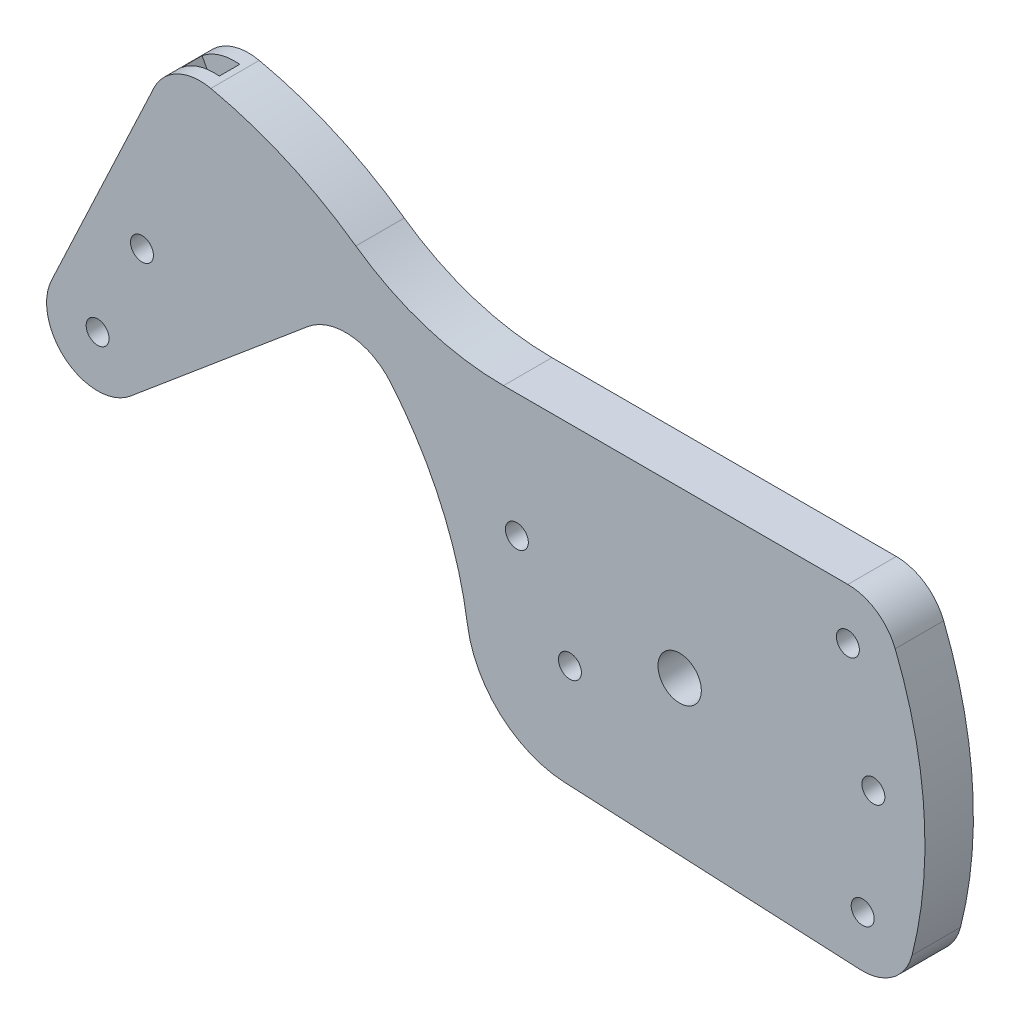
SolidWorks part; units mm, degrees
ref_plane "Front Plane" through (0, 0, 0) normal (0, 0, 1) x (1, 0, 0)
ref_plane "Top Plane" through (0, 0, 0) normal (0, 1, 0) x (1, 0, 0)
ref_plane "Right Plane" through (0, 0, 0) normal (1, 0, 0) x (0, 0, -1)
sketch "Sketch1" plane through (0, 0, 0) normal (0, 0, 1) x (1, 0, 0)
  line L1 (-4.25, -4.25) -> (4.25, -4.25) construction
  line L2 (-4.25, -4.25) -> (-4.25, 4.25) construction
  line L3 (-4.25, 4.25) -> (4.25, 4.25) construction
  line L4 (4.25, -4.25) -> (4.25, 4.25) construction
  line L5 (-4.25, -4.25) -> (4.25, 4.25) construction
  line L6 (-4.25, 4.25) -> (4.25, -4.25) construction
  line L7 (35.3984, -31.7883) -> (-22.5002, -28.984)
  line L9 (-114.4671, 24.4556) -> (-123.1671, 5.9556)
  line L10 (-107.6899, -5.9604) -> (-72.8648, 23.2613)
  line L11 (-114.4671, 24.4556) -> (-103.0859, 48.6569)
  line L16 (-65.4725, 14.4515) -> (-108.3178, -21.5) construction
  line L17 (50.9822, -33.5) -> (-177.2181, -33.5) construction
  line L20 (-34.5382, 32.4) -> (32.9822, 32.4)
  circle A0 centre (0, 0) radius 4.25
  circle A1 centre (-31.9178, 8.2) radius 2.25
  circle A2 centre (-21.5178, -8.7) radius 2.25
  circle A3 centre (32.9822, 22.4) radius 2.25
  circle A4 centre (37.9822, -0.1) radius 2.25
  circle A5 centre (35.8822, -21.8) radius 2.25
  circle A6 centre (35.8822, -21.8) radius 2.25 construction
  circle A7 centre (37.9822, -0.1) radius 2.25 construction
  circle A8 centre (32.9822, 22.4) radius 2.25 construction
  circle A9 centre (-31.9178, 8.2) radius 2.25 construction
  circle A10 centre (-21.5178, -8.7) radius 2.25 construction
  arc A12 (-41.6083, -11.6627) -> (-22.5002, -28.984) centre (-21.5178, -8.7) ccw
  arc A13 (32.5913, -31.6523) -> (28.0429, 32.4) centre (-33.3577, -4.1478) ccw construction
  arc A14 (45.5723, -24.2704) -> (42.2664, 26.1153) centre (-33.3577, -4.1478) ccw
  arc A15 (35.3984, -31.7883) -> (45.5723, -24.2704) centre (35.8822, -21.8) ccw
  arc A16 (42.2664, 26.1153) -> (32.9822, 32.4) centre (32.9822, 22.4) ccw
  circle A17 centre (-105.4178, 20.2) radius 2.25
  circle A18 centre (-33.3577, -4.1478) radius 81.4546 construction
  circle A19 centre (-114.1178, 1.7) radius 2.25
  circle A21 centre (-105.4178, 20.2) radius 2.25 construction
  circle A22 centre (-114.1178, 1.7) radius 2.25 construction
  circle A23 centre (-105.4178, 20.2) radius 10 construction
  arc A24 (-123.1671, 5.9556) -> (-107.6899, -5.9604) centre (-114.1178, 1.7) ccw
  arc A27 (-91.9187, 54.1744) -> (-103.0859, 48.6569) centre (-94.0366, 44.4013) ccw
  circle A31 centre (-33.3577, -4.1478) radius 71.4546 construction
  arc A32 (-41.6083, -11.6627) -> (-56.6627, 21.8438) centre (-108.3178, -21.5) ccw
  arc A33 (-31.0568, -26.628) -> (-91.9187, 54.1744) centre (-108.3178, -21.5) ccw
  arc A34 (-63.487, 41.6328) -> (-34.5382, 32.4) centre (-34.5382, 82.4) ccw
  arc A35 (-56.6627, 21.8438) -> (-72.8648, 23.2613) centre (-65.4725, 14.4515) ccw
  circle A36 centre (-65.4725, 14.4515) radius 10.5004 construction
  circle A37 centre (-108.3178, -21.5) radius 67.4309 construction
  circle A38 centre (-108.3178, -21.5) radius 77.4309 construction
  circle A39 centre (-108.3178, -21.5) radius 10.5004 construction
  circle A40 centre (-108.3178, -21.5) radius 11.5004 construction
  circle A41 centre (0, 0) radius 33 construction
  point P35 (50.3427, -4.5217)
  point P37 (37.1696, 16.7103)
  point P54 (-36.0565, -0.0269)
  point P75 (-40.8381, -1.4887)
  dimension "D1" = 8.5
  dimension "D3" = 10
  dimension "D5" = 50
  dimension "D7" = 40
  dimension "D4" = 10
  dimension "D2" = 10
  dimension "D8" = 1
extrude "Boss-Extrude1" add sketch "Sketch1" along normal mid plane 9.5 contours A0 L4 L3 | A0 L1 L4 | A0 L2 L1 | A0 L3 L2 | A35 A32 A12 A33 A27 L11 L9 A24 L10 A17 A19
sketch "Sketch2" plane through (0, 0, 0) normal (0, 0, 1) x (1, 0, 0)
  line L0 (-94.0366, 44.4013) -> (-96.9145, 53.9782) construction
  line L1 (-78.2271, 18.7618) -> (-72.8648, 23.2613)
  line L2 (-94.0366, 44.4013) -> (-84.6999, 13.3304) construction
  line L3 (-92.0846, 44.9879) -> (-78.2271, 18.7618)
  line L4 (-95.0124, 54.3536) -> (-94.0366, 44.4013) construction
  line L5 (-94.0366, 44.4013) -> (-90.5122, 8.4534) construction
  line L6 (-98.7084, 53.2429) -> (-94.0366, 44.4013) construction
  line L7 (-94.0366, 44.4013) -> (-79.7943, 17.4467) construction
  line L8 (-100.3823, 52.1299) -> (-95.9887, 43.8147)
  line L9 (-93.0022, 54.3476) -> (-92.0846, 44.9879)
  line L12 (-92.369, 6.8953) -> (-78.2271, 18.7618)
  line L13 (-107.6899, -5.9604) -> (-72.8648, 23.2613) construction
  line L14 (-101.3327, 53.9285) -> (-91.0539, 34.4751) construction
  line L15 (-93.2007, 56.3721) -> (-91.0539, 34.4751) construction
  line L16 (-95.9887, 43.8147) -> (-92.369, 6.8953)
  line L18 (-97.0194, 54.3274) -> (-78.2271, 18.7618) construction
  line L19 (-97.0194, 54.3274) -> (-92.369, 6.8953) construction
  line L20 (-92.369, 6.8953) -> (-107.6899, -5.9604)
  line L22 (-94.0366, 44.4013) -> (-90.3786, 7.0905) construction
  line L23 (-94.0366, 44.4013) -> (-79.9955, 17.8274) construction
  arc A0 (-93.0022, 54.3476) -> (-100.3823, 52.1299) centre (-94.0366, 44.4013) ccw
  arc A1 (-95.0124, 54.3536) -> (-98.7084, 53.2429) centre (-94.0366, 44.4013) ccw construction
  arc A2 (-93.2007, 56.3721) -> (-101.3327, 53.9285) centre (-94.0366, 44.4013) ccw construction
  arc A3 (-91.9187, 54.1744) -> (-103.0859, 48.6569) centre (-94.0366, 44.4013) ccw construction
  point P33 (-96.9145, 53.9782)
  dimension "D3" = 7
  dimension "D4" = 20
  dimension "D1" = 2
  dimension "D2" = 2
extrude "Cut-Extrude1" cut sketch "Sketch2" against normal mid plane 4
